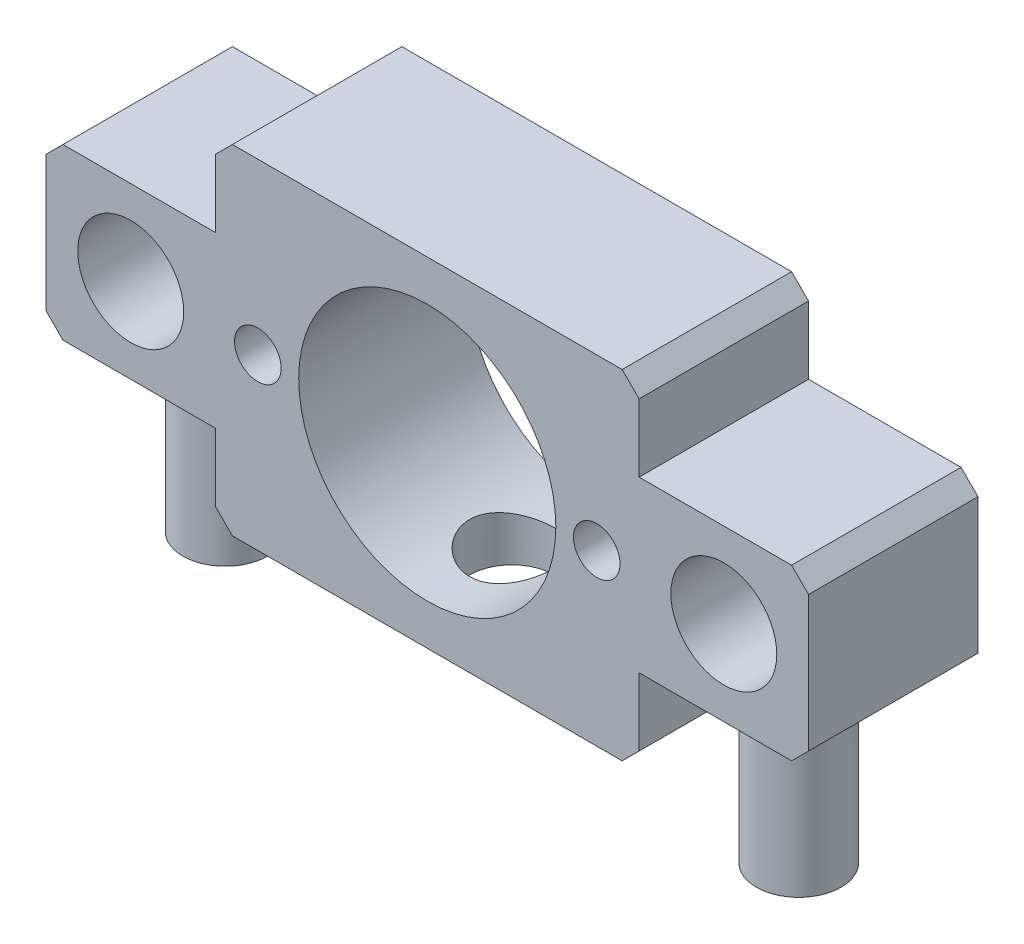
SolidWorks part; units mm, degrees
ref_plane "Front Plane" through (0, 0, 0) normal (0, 0, 1) x (1, 0, 0)
ref_plane "Top Plane" through (0, 0, 0) normal (0, 1, 0) x (1, 0, 0)
ref_plane "Right Plane" through (0, 0, 0) normal (1, 0, 0) x (0, 0, -1)
ref_plane "Plane1" through (0, 0, 10) normal (0, 0, 1) x (1, 0, 0)
sketch "Sketch1" plane through (0, 0, 10) normal (0, 0, 1) x (1, 0, 0)
  line L0 (45, 20) -> (-45, 20)
  line L1 (-45, 20) -> (-45, -20)
  line L2 (-45, -20) -> (45, -20)
  line L3 (45, -20) -> (45, 20)
extrude "Boss-Extrude1" add sketch "Sketch1" against normal blind 20
sketch "Sketch2" plane through (0, 0, -10) normal (0, 0, -1) x (-1, 0, 0)
  line L0 (25, 10) -> (45, 10)
  line L1 (45, 10) -> (45, 20)
  line L2 (45, 20) -> (25, 20)
  line L3 (25, 20) -> (25, 10)
extrude "Cut-Extrude1" cut sketch "Sketch2" against normal through all
sketch "Sketch3" plane through (0, 0, -10) normal (0, 0, -1) x (-1, 0, 0)
  line L0 (25, -10) -> (25, -20)
  line L1 (25, -20) -> (45, -20)
  line L2 (45, -20) -> (45, -10)
  line L3 (45, -10) -> (25, -10)
extrude "Cut-Extrude2" cut sketch "Sketch3" against normal through all
sketch "Sketch4" plane through (0, 0, -10) normal (0, 0, -1) x (-1, 0, 0)
  line L0 (-25, -20) -> (-25, -10)
  line L1 (-25, -10) -> (-45, -10)
  line L2 (-45, -10) -> (-45, -20)
  line L3 (-45, -20) -> (-25, -20)
extrude "Cut-Extrude3" cut sketch "Sketch4" against normal through all
sketch "Sketch5" plane through (0, 0, -10) normal (0, 0, -1) x (-1, 0, 0)
  line L0 (-25, 10) -> (-25, 20)
  line L1 (-25, 20) -> (-45, 20)
  line L2 (-45, 20) -> (-45, 10)
  line L3 (-45, 10) -> (-25, 10)
extrude "Cut-Extrude4" cut sketch "Sketch5" against normal through all
hole_wizard "Ø5.0 (5) Diameter Hole1" positions "Sketch7" profile "Sketch6" hole size "Ø5.0" standard "ANSI Metric"
sketch "Sketch7" plane through (0, 0, 10) normal (0, 0, 1) x (1, 0, 0)
  point P0 (20, 0)
  point P1 (-20, 0)
sketch "Sketch6" plane through (20, 0, 10) normal (1, 0, 0) x (0, -1, 0)
  line L0 (0, 0) -> (0, 12)
  line L1 (0, 12) -> (2.5, 12)
  line L2 (2.5, 12) -> (2.5, 0)
  line L5 (2.5, 0) -> (0, 0)
  line L10 (0, 12) -> (-2.5, 12) construction
  line L11 (0, -6.35) -> (0, 107.95) construction
  dimension "Hole Dia." = 5
  dimension "Hole Depth" = 12
  dimension "Drill Angle" = 180
hole_wizard "M27 Clearance Hole1" positions "Sketch9" profile "Sketch8" hole size "M27" standard "ANSI Metric"
sketch "Sketch9" plane through (0, 0, 10) normal (0, 0, 1) x (1, 0, 0)
  point P0 (0, 0)
sketch "Sketch8" plane through (0, 0, 10) normal (1, 0, 0) x (0, -1, 0)
  line L0 (0, 0) -> (0, 20)
  line L1 (0, 20) -> (14.9246, 20)
  line L2 (14.9246, 20) -> (14.9246, 0)
  line L5 (14.9246, 0) -> (0, 0)
  line L11 (0, -6.35) -> (0, 107.95) construction
  dimension "Thru Hole Dia." = 29.8492
  dimension "Thru Hole Depth" = 20
hole_wizard "Ø10.0 (10) Diameter Hole1" positions "Sketch11" profile "Sketch10" hole size "Ø10.0" standard "ANSI Metric"
sketch "Sketch11" plane through (0, -20, 0) normal (0, -1, 0) x (-1, 0, 0)
  point P0 (0, 0)
sketch "Sketch10" plane through (0, -20, 0) normal (1, 0, 0) x (0, 0, -1)
  line L0 (0, 0) -> (0, 5.0754)
  line L1 (0, 5.0754) -> (5, 5.0754)
  line L2 (5, 5.0754) -> (5, 0)
  line L5 (5, 0) -> (0, 0)
  line L11 (0, -6.35) -> (0, 107.95) construction
  dimension "Thru Hole Dia." = 10
  dimension "Thru Hole Depth" = 5.0754
hole_wizard "Ø12.0 (12) Diameter Hole1" positions "Sketch13" profile "Sketch12" hole size "Ø12.0" standard "ANSI Metric"
sketch "Sketch13" plane through (0, 0, -10) normal (0, 0, -1) x (-1, 0, 0)
  point P0 (35, 0)
  point P1 (-35, 0)
sketch "Sketch12" plane through (-35, 0, -10) normal (1, 0, 0) x (0, 1, 0)
  line L0 (0, 0) -> (0, 20)
  line L1 (0, 20) -> (6, 20)
  line L2 (6, 20) -> (6, 0)
  line L5 (6, 0) -> (0, 0)
  line L11 (0, -6.35) -> (0, 107.95) construction
  dimension "Thru Hole Dia." = 12
  dimension "Thru Hole Depth" = 20
chamfer "Chamfer1" distance 2 angle 45 8 edges at (-25, 20, 0) (25, -20, 0) (-25, -20, 0) (45, -10, 0) (25, 20, 0) (-45, -10, 0) (45, 10, 0) (-45, 10, 0)
sketch "Sketch17" plane through (0, 10, 0) normal (0, 1, 0) x (1, 0, 0)
  circle A0 centre (-33.8464, 0) radius 5
  circle A1 centre (33.8464, 0) radius 5
  dimension "D1" = 10
  dimension "D2" = 10
sketch "Sketch18" plane through (0, 0, 10) normal (0, 0, 1) x (1, 0, 0)
  circle A0 centre (-35, 0) radius 6.25
  circle A1 centre (35, 0) radius 6.25
  dimension "D1" = 12.5
  dimension "D2" = 12.5
extrude "Cut-Extrude6" cut sketch "Sketch18" against normal blind 100
sketch "Sketch20" plane through (0, 0, 10) normal (0, 0, 1) x (1, 0, 0)
  circle A0 centre (0, 0) radius 15.175
  dimension "D1" = 30.35
extrude "Cut-Extrude7" cut sketch "Sketch20" against normal blind 100
sketch "Sketch21" plane through (0, 0, 10) normal (0, 0, 1) x (1, 0, 0)
  circle A0 centre (-20, 0) radius 2.75
  circle A1 centre (20, 0) radius 2.75
  dimension "D1" = 5.5
extrude "Cut-Extrude8" cut sketch "Sketch21" against normal blind 12
sketch "Sketch23" plane through (0, -10, 0) normal (0, -1, 0) x (1, 0, 0)
  circle A0 centre (-33.8464, 0) radius 5
  circle A1 centre (33.8464, 0) radius 5
extrude "Boss-Extrude2" add sketch "Sketch23" along normal blind 20
